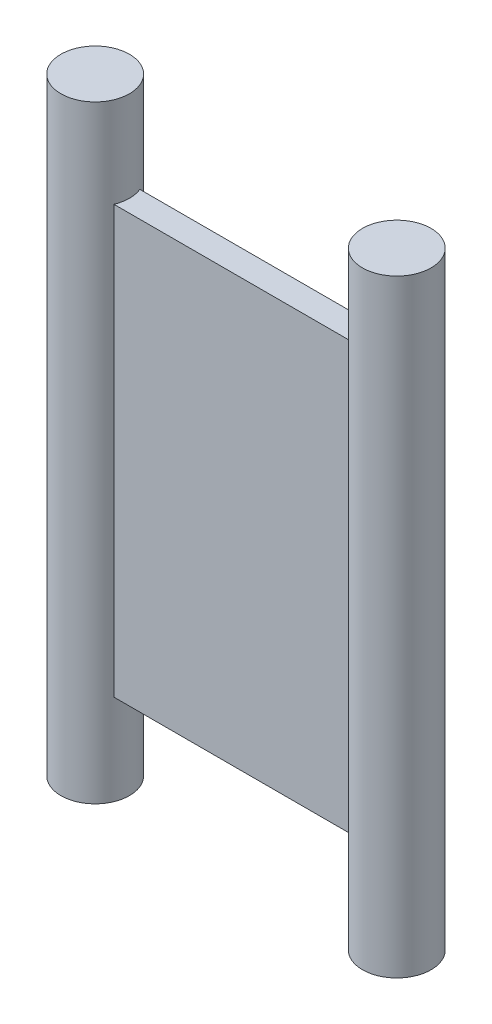
SolidWorks part; units mm, degrees
ref_plane "Front Plane" through (0, 0, 0) normal (0, 0, 1) x (1, 0, 0)
ref_plane "Top Plane" through (0, 0, 0) normal (0, 1, 0) x (1, 0, 0)
ref_plane "Right Plane" through (0, 0, 0) normal (1, 0, 0) x (0, 0, -1)
sketch "Sketch1" plane through (0, 0, 0) normal (0, 1, 0) x (1, 0, 0)
  line L1 (5.83, 0.5) -> (-5.83, 0.5)
  line L2 (5.83, 0.5) -> (5.83, -0.5)
  line L3 (5.83, -0.5) -> (-5.83, -0.5)
  line L4 (-5.83, 0.5) -> (-5.83, -0.5)
  line L5 (5.83, 0.5) -> (-5.83, -0.5) construction
  line L6 (5.83, -0.5) -> (-5.83, 0.5) construction
  point P0 (0, 0)
  dimension "D1" = 11.66
  dimension "D3" = 1
extrude "Boss-Extrude1" add sketch "Sketch1" along normal blind 16.5
ref_plane "Plane1" through (0, 8.25, 0) normal (0, 1, 0) x (1, 0, 0)
sketch "Sketch2" plane through (0, 8.25, 0) normal (0, 1, 0) x (1, 0, 0)
  line L0 (5.83, -0.5) -> (5.83, 0.5) construction
  line L1 (-5.83, 0.5) -> (-5.83, -0.5) construction
  line L2 (5.83, -0.5) -> (5.83, 0.5) construction
  line L3 (-5.83, 0.5) -> (-5.83, -0.5) construction
  circle A0 centre (-5.83, 0) radius 1.325
  circle A1 centre (5.83, 0) radius 1.325
  dimension "D1" = 2.65
extrude "Boss-Extrude2" add sketch "Sketch2" along normal mid plane 23.5
